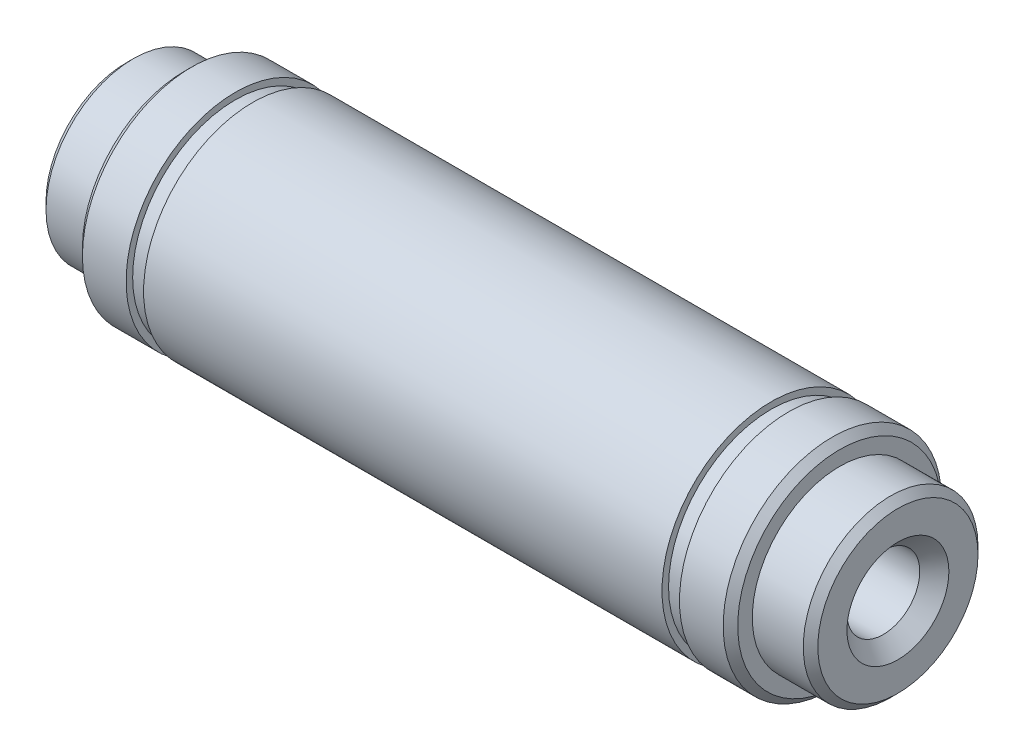
SolidWorks part; units mm, degrees
material "1.7005 (45Cr2)"
ref_plane "Спереди" through (0, 0, 0) normal (0, 0, 1) x (1, 0, 0)
ref_plane "Сверху" through (0, 0, 0) normal (0, 1, 0) x (1, 0, 0)
ref_plane "Справа" through (0, 0, 0) normal (1, 0, 0) x (0, 0, -1)
sketch "Эскиз1" plane through (0, 0, 0) normal (0, 0, 1) x (1, 0, 0)
  line L0 (0, 0) -> (-27569.947, 0) construction
  line L1 (-26.5, 0) -> (-26.5, 6)
  line L2 (-26.5, 6) -> (-22.5, 6)
  line L3 (-22.5, 6) -> (-22.5, 7.5)
  line L4 (-22.5, 7.5) -> (22.5, 7.5)
  line L5 (22.5, 7.5) -> (22.5, 6)
  line L6 (22.5, 6) -> (26.5, 6)
  line L7 (26.5, 6) -> (26.5, 0)
  line L8 (26.5, 0) -> (-26.5, 0)
  line L9 (0, 0) -> (0, 50000) construction
  dimension "D1" = 45
  dimension "D2" = 53
  dimension "D3" = 15
  dimension "D4" = 12
revolve "Повернуть1" add sketch "Эскиз1" angle 360 about L0
sketch "Эскиз4" plane through (-26.5, 0, 0) normal (-1, 0, 0) x (0, 0, 1)
  point P0 (0, 0)
hole_wizard "Отверстие обработанное метчиком M61" positions "Эскиз4" profile "Эскиз3" tap size "M6" standard "DIN"
sketch "Эскиз3" plane through (-26.5, 0, 0) normal (0, 1, 0) x (0, 0, 1)
  line L0 (0, 0) -> (0, 18.5022)
  line L1 (0, 18.5022) -> (2.5, 17)
  line L2 (2.5, 17) -> (2.5, 1)
  line L3 (2.5, 1) -> (3.5, 0)
  line L5 (3.5, 0) -> (0, 0)
  line L6 (-2.5, 1) -> (-3.5, 0) construction
  line L10 (0, 18.5022) -> (-2.5, 17) construction
  line L11 (0, -6.35) -> (0, 107.95) construction
  dimension "Диаметр сверла" = 5
  dimension "Глубина сверла" = 17
  dimension "Диаметр передней зенковки" = 7
  dimension "Угол передней зенковки" = 90
  dimension "Угол заточки сверла" = 118
cosmetic thread "Отверстие резьбы3" parameters "D1"=12, "D2"=6
sketch "Эскиз8" plane through (26.5, 0, 0) normal (1, 0, 0) x (0, 0, -1)
  point P0 (0, 0)
hole_wizard "Отверстие обработанное метчиком M62" positions "Эскиз8" profile "Эскиз7" tap size "M6" standard "ISO"
cosmetic thread "Отверстие резьбы4" parameters "D1"=12, "D2"=6
sketch "Эскиз7" plane through (26.5, 0, 0) normal (0, 1, 0) x (0, 0, -1)
  line L0 (0, 0) -> (0, 18.5022)
  line L1 (0, 18.5022) -> (2.5, 17)
  line L2 (2.5, 17) -> (2.5, 1)
  line L3 (2.5, 1) -> (3.5, 0)
  line L5 (3.5, 0) -> (0, 0)
  line L6 (-2.5, 1) -> (-3.5, 0) construction
  line L10 (0, 18.5022) -> (-2.5, 17) construction
  line L11 (0, -6.35) -> (0, 107.95) construction
  dimension "Диаметр сверла" = 5
  dimension "Глубина сверла" = 17
  dimension "Диаметр передней зенковки" = 7
  dimension "Угол передней зенковки" = 90
  dimension "Угол заточки сверла" = 118
sketch "Эскиз5" plane through (0, 0, 0) normal (0, 0, 1) x (1, 0, 0)
  line L0 (-19, 7.5) -> (-19, 7.05)
  line L1 (22.5, 7.5) -> (-22.5, 7.5) construction
  line L2 (-19, 7.05) -> (-17.8, 7.05)
  line L3 (-17.8, 7.05) -> (-17.8, 7.5)
  line L4 (-17.8, 7.5) -> (-19, 7.5)
  line L5 (0, 0) -> (0, 50000) construction
  line L6 (17.8, 7.5) -> (19, 7.5)
  line L7 (17.8, 7.05) -> (17.8, 7.5)
  line L8 (19, 7.05) -> (17.8, 7.05)
  line L9 (19, 7.5) -> (19, 7.05)
  line L10 (0, 0) -> (-50000, 0) construction
  dimension "D1" = 1.2
  dimension "D2" = 14.1
  dimension "D3" = 17.8
revolve "Вырез-Повернуть1" cut sketch "Эскиз5" angle 360 about L10
chamfer "Фаска2" distance 0.5 angle 45 4 edges at (22.5, 0, -7.5) (-22.5, 0, -7.5) (26.5, 0, -6) (-26.5, 0, -6)
